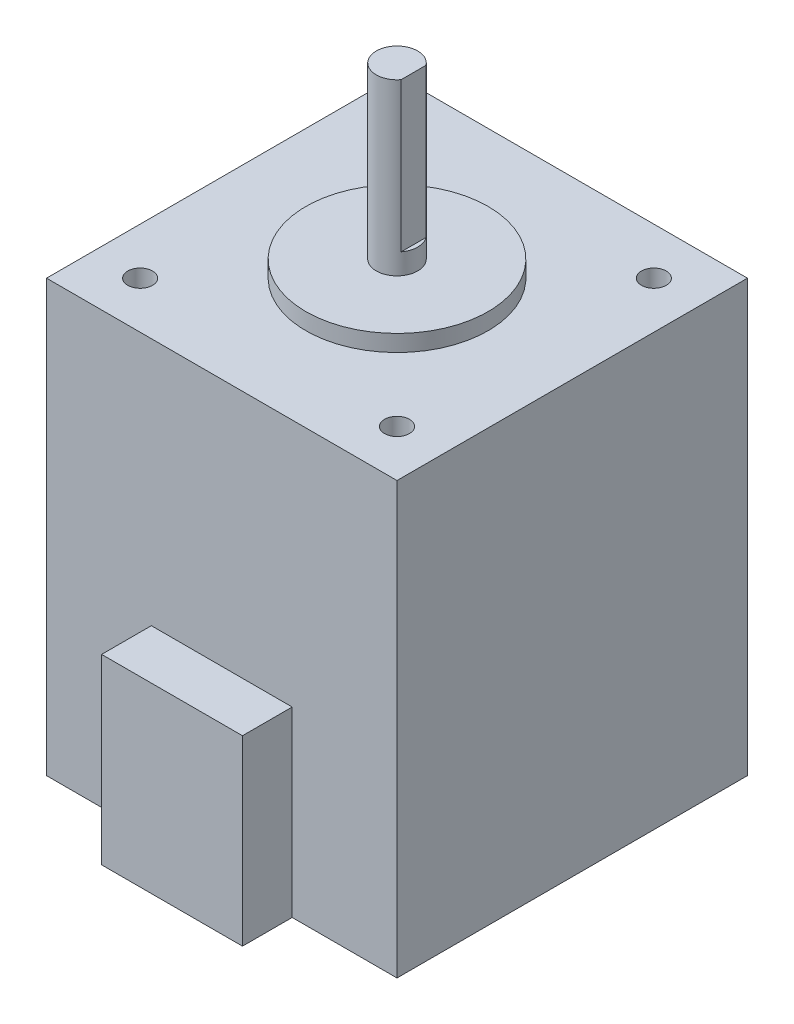
SolidWorks part; units mm, degrees
ref_plane "前视基准面" through (0, 0, 0) normal (0, 0, 1) x (1, 0, 0)
ref_plane "上视基准面" through (0, 0, 0) normal (0, 1, 0) x (1, 0, 0)
ref_plane "右视基准面" through (0, 0, 0) normal (1, 0, 0) x (0, 0, -1)
sketch "草图1" plane through (0, 0, 0) normal (0, 1, 0) x (1, 0, 0)
  line L1 (-21.15, -21.15) -> (21.15, -21.15)
  line L2 (-21.15, -21.15) -> (-21.15, 21.15)
  line L3 (-21.15, 21.15) -> (21.15, 21.15)
  line L4 (21.15, -21.15) -> (21.15, 21.15)
  line L5 (-21.15, -21.15) -> (21.15, 21.15) construction
  line L6 (-21.15, 21.15) -> (21.15, -21.15) construction
  point P0 (0, 0)
  dimension "D1" = 42.3
extrude "凸台-拉伸1" add sketch "草图1" along normal blind 52
sketch "草图2" plane through (0, 52, 0) normal (0, 1, 0) x (1, 0, 0)
  line L1 (-15.5, -15.5) -> (15.5, -15.5) construction
  line L2 (-15.5, -15.5) -> (-15.5, 15.5) construction
  line L3 (-15.5, 15.5) -> (15.5, 15.5) construction
  line L4 (15.5, -15.5) -> (15.5, 15.5) construction
  line L5 (-15.5, -15.5) -> (15.5, 15.5) construction
  line L6 (-15.5, 15.5) -> (15.5, -15.5) construction
  circle A0 centre (-15.5, 15.5) radius 1.5
  circle A1 centre (15.5, 15.5) radius 1.5
  circle A2 centre (15.5, -15.5) radius 1.5
  circle A3 centre (-15.5, -15.5) radius 1.5
  point P0 (0, 0)
  point P7 (0, 0)
  point P16 (0, 0)
  dimension "D3" = 3
  dimension "D1" = 31
  dimension "D2" = 4
extrude "切除-拉伸1" cut sketch "草图2" against normal blind 4
sketch "草图3" plane through (0, 52, 0) normal (0, 1, 0) x (1, 0, 0)
  circle A0 centre (0, 0) radius 11
  dimension "D1" = 22
extrude "凸台-拉伸2" add sketch "草图3" along normal blind 2
sketch "草图4" plane through (0, 54, 0) normal (0, 1, 0) x (1, 0, 0)
  circle A0 centre (0, 0) radius 2.5
  point P3 (0, 0)
  dimension "D1" = 5
extrude "凸台-拉伸3" add sketch "草图4" along normal blind 20.5
sketch "草图5" plane through (0, 74.5, 0) normal (0, 1, 0) x (1, 0, 0)
  line L0 (-2.5, 0) -> (2, 0) construction
  line L1 (2, 1.5) -> (2, -1.5)
  circle A0 centre (0, 0) radius 2.5 construction
  circle A1 centre (0, 0) radius 2.5 construction
  arc A2 (2, -1.5) -> (2, 1.5) centre (0, 0) ccw
  circle M2 centre (0, 0) radius 2.5
  dimension "D1" = 4.5
extrude "切除-拉伸4" cut sketch "草图5" against normal blind 18 contours L1 M2
sketch "草图6" plane through (0, 0, 21.15) normal (0, 0, 1) x (1, 0, 0)
  line L0 (-21.15, 0) -> (21.15, 0) construction
  line L1 (-8.5, 0) -> (8.5, 0)
  line L2 (-8.5, 0) -> (-8.5, 22)
  line L3 (-8.5, 22) -> (8.5, 22)
  line L4 (8.5, 0) -> (8.5, 22)
  dimension "D1" = 17
  dimension "D2" = 22
extrude "凸台-拉伸4" add sketch "草图6" along normal blind 6
